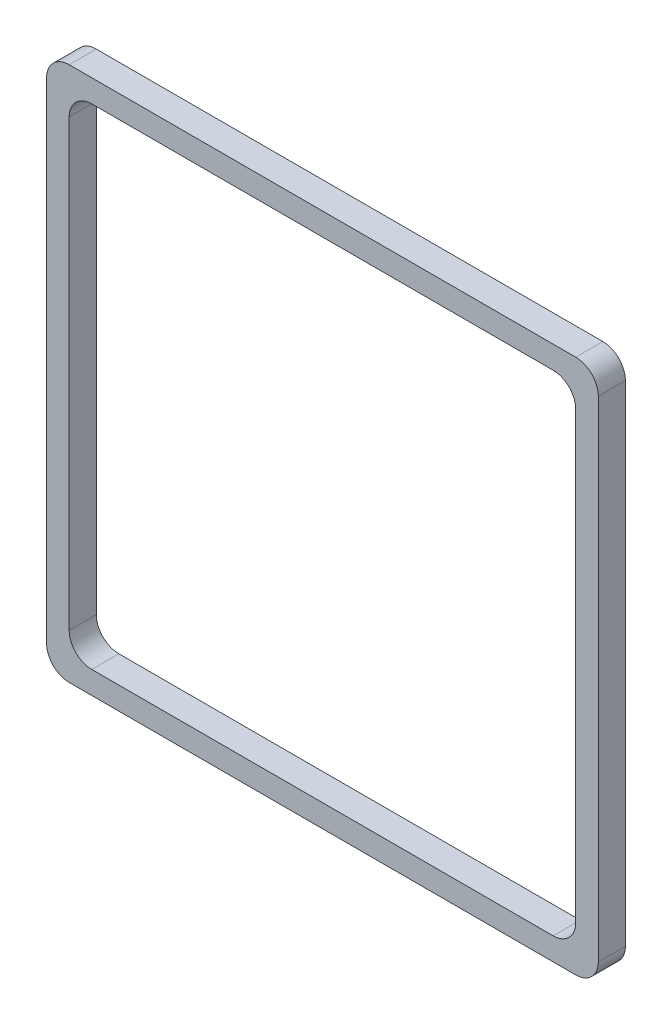
SolidWorks part; units mm, degrees
ref_plane "前视基准面" through (0, 0, 0) normal (0, 0, 1) x (1, 0, 0)
ref_plane "上视基准面" through (0, 0, 0) normal (0, 1, 0) x (1, 0, 0)
ref_plane "右视基准面" through (0, 0, 0) normal (1, 0, 0) x (0, 0, -1)
sketch "草图1" plane through (0, 0, 0) normal (0, 0, 1) x (1, 0, 0)
  line L1 (-10.1959, 177.8409) -> (194.1041, 177.8409)
  line L2 (-20.1959, 167.8409) -> (-20.1959, -29.0591)
  line L3 (-10.1959, -39.0591) -> (194.1041, -39.0591)
  line L4 (204.1041, 167.8409) -> (204.1041, -29.0591)
  line L5 (-20.1959, 187.8409) -> (204.1041, 187.8409)
  line L6 (-30.1959, 177.8409) -> (-30.1959, -39.0591)
  line L7 (-20.1959, -49.0591) -> (204.1041, -49.0591)
  line L8 (214.1041, 177.8409) -> (214.1041, -39.0591)
  arc A0 (194.1041, -39.0591) -> (204.1041, -29.0591) centre (194.1041, -29.0591) ccw
  arc A1 (-20.1959, -29.0591) -> (-10.1959, -39.0591) centre (-10.1959, -29.0591) ccw
  arc A2 (-10.1959, 177.8409) -> (-20.1959, 167.8409) centre (-10.1959, 167.8409) ccw
  arc A3 (194.1041, 177.8409) -> (204.1041, 167.8409) centre (194.1041, 167.8409) cw
  arc A4 (204.1041, 187.8409) -> (214.1041, 177.8409) centre (204.1041, 177.8409) cw
  arc A5 (204.1041, -49.0591) -> (214.1041, -39.0591) centre (204.1041, -39.0591) ccw
  arc A6 (-30.1959, -39.0591) -> (-20.1959, -49.0591) centre (-20.1959, -39.0591) ccw
  arc A7 (-20.1959, 187.8409) -> (-30.1959, 177.8409) centre (-20.1959, 177.8409) ccw
  dimension "D1" = 10
  dimension "D2" = 10
  dimension "D3" = 10
  dimension "D4" = 10
  dimension "D5" = 10
  dimension "D6" = 196.9
  dimension "D7" = 204.3
extrude "凸台-拉伸1" add sketch "草图1" along normal blind 12
